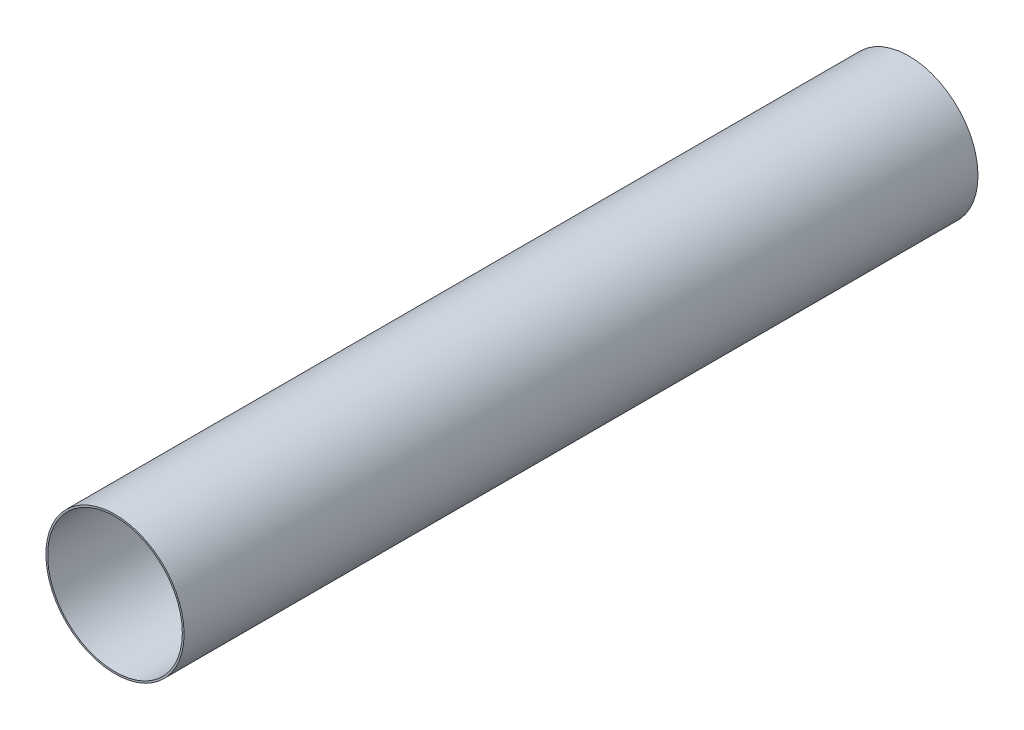
SolidWorks part; units mm, degrees
material "E-Glass Fiber"
ref_plane "Front" through (0, 0, 0) normal (0, 0, 1) x (1, 0, 0)
ref_plane "Top" through (0, 0, 0) normal (0, 1, 0) x (1, 0, 0)
ref_plane "Right" through (0, 0, 0) normal (1, 0, 0) x (0, 0, -1)
sketch "Sketch1" plane through (0, 0, 0) normal (0, 0, 1) x (1, 0, 0)
  circle A0 centre (0, 0) radius 78.35
  circle A1 centre (0, 0) radius 76.35
  dimension "D1" = 2
  dimension "D2" = 152.7
extrude "Boss-Extrude1" add sketch "Sketch1" along normal blind 900
